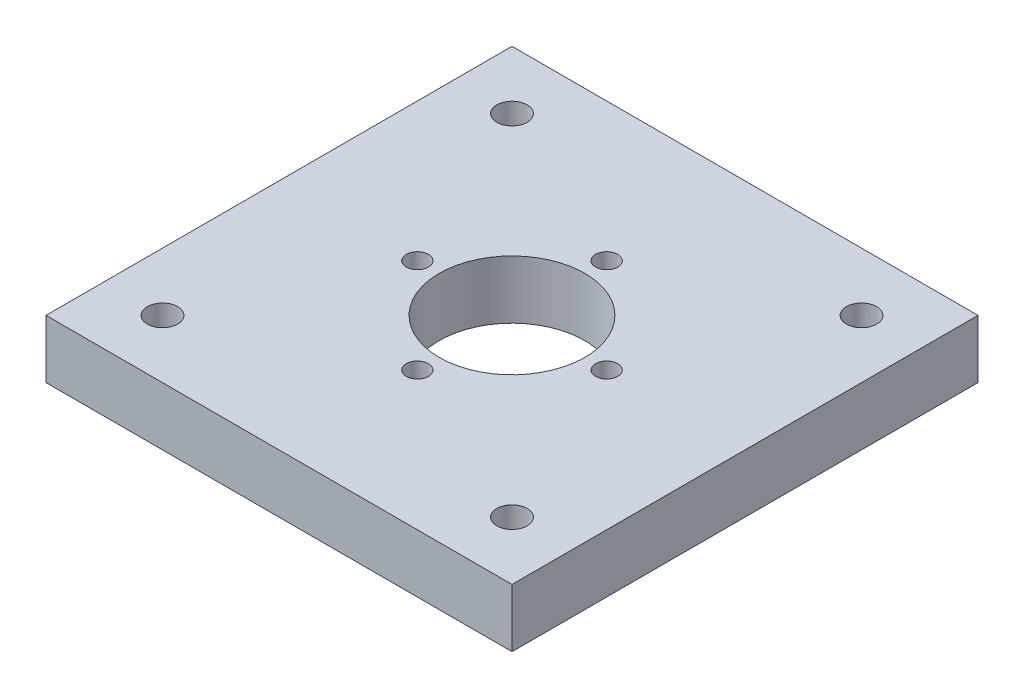
SolidWorks part; units mm, degrees
ref_plane "Front Plane" through (0, 0, 0) normal (0, 0, 1) x (1, 0, 0)
ref_plane "Top Plane" through (0, 0, 0) normal (0, 1, 0) x (1, 0, 0)
ref_plane "Right Plane" through (0, 0, 0) normal (1, 0, 0) x (0, 0, -1)
sketch "Sketch2" plane through (0, 0, 0) normal (0, 1, 0) x (1, 0, 0)
  line L1 (-50.8, 50.8) -> (50.8, 50.8)
  line L2 (-50.8, 50.8) -> (-50.8, -50.8)
  line L3 (-50.8, -50.8) -> (50.8, -50.8)
  line L4 (50.8, 50.8) -> (50.8, -50.8)
  line L5 (-50.8, 50.8) -> (50.8, -50.8) construction
  line L6 (-50.8, -50.8) -> (50.8, 50.8) construction
  point P0 (0, 0)
  dimension "D1" = 101.6
  dimension "D2" = 101.6
extrude "Boss-Extrude1" add sketch "Sketch2" along normal mid plane 12.7
sketch "Sketch3" plane through (0, 6.35, 0) normal (0, 1, 0) x (1, 0, 0)
  line L2 (-50.8, 50.8) -> (-50.8, -50.8) construction
  line L3 (-50.8, -50.8) -> (50.8, -50.8) construction
  line L4 (0, 0) -> (15.0672, 0) construction
  line L5 (0, 0) -> (0, 15.3521) construction
  circle A0 centre (-38.1, -38.1) radius 3.302
  circle A2 centre (-38.1, 38.1) radius 3.302
  circle A3 centre (38.1, -38.1) radius 3.302
  circle A4 centre (38.1, 38.1) radius 3.302
  dimension "D3" = 12.7
  dimension "D1" = 6.604
  dimension "D2" = 12.7
extrude "Cut-Extrude1" cut sketch "Sketch3" against normal through all
sketch "Sketch4" plane through (0, 6.35, 0) normal (0, 1, 0) x (1, 0, 0)
  circle A0 centre (0, 0) radius 15.875
  circle A1 centre (0, 0) radius 20.6375 construction
  circle A2 centre (0, 20.6375) radius 2.413
  circle A3 centre (20.6375, 0) radius 2.413
  circle A4 centre (0, -20.6375) radius 2.413
  circle A5 centre (-20.6375, 0) radius 2.413
  point P6 (-7.4003, -19.2651)
  point P7 (0, 0)
  point P15 (0, 0)
  dimension "D1" = 31.75
  dimension "D2" = 41.275
  dimension "D3" = 4.826
  dimension "D4" = 4
extrude "Cut-Extrude2" cut sketch "Sketch4" against normal through all
